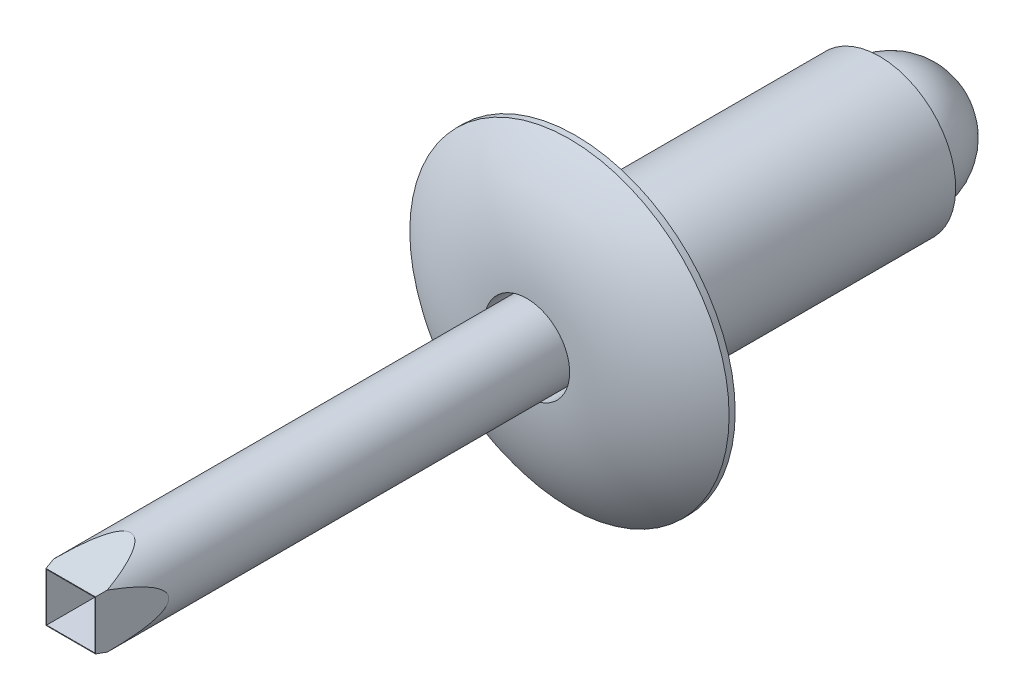
SolidWorks part; units mm, degrees
material "1060 Alloy"
ref_plane "Front" through (0, 0, 0) normal (0, 0, 1) x (1, 0, 0)
ref_plane "Top" through (0, 0, 0) normal (0, 1, 0) x (1, 0, 0)
ref_plane "Right" through (0, 0, 0) normal (1, 0, 0) x (0, 0, -1)
sketch "Sketch1" plane through (0, 0, 0) normal (1, 0, 0) x (0, 0, -1)
  line L0 (-21.082, 0) -> (-2.032, 0) construction
  line L1 (-2.032, 0) -> (0, 0) construction
  line L2 (0, 0) -> (12.7, 0) construction
  line L3 (12.7, 0) -> (15.748, 0) construction
  line L8 (0, 6.6675) -> (0, -6.6675) construction
  line L9 (12.7, 3.175) -> (12.7, -3.175) construction
  dimension "Length" = 12.7
  dimension "Head Height" = 2.032
  dimension "D5" = 3.048
  dimension "D9" = 19.05
  dimension "Diameter" = 6.35
  dimension "Head Diameter" = 13.335
sketch "Sketch2" plane through (0, 0, 0) normal (1, 0, 0) x (0, 0, -1)
  line L0 (-21.082, 1.5875) -> (-21.082, 0) construction
  line L1 (-21.082, 1.5875) -> (0, 1.5875) construction
  line L2 (0, 6.6675) -> (0, -6.6675) construction
  line L3 (0, 0) -> (0, 6.6675) construction
  line L4 (-2.032, 0) -> (-2.032, -1.8472) construction
  line L5 (12.7, 3.175) -> (0, 3.175)
  line L6 (12.7, 3.175) -> (12.7, 0) construction
  line L7 (15.748, 0) -> (15.748, 3.175) construction
  line L8 (12.7, 3.175) -> (12.7, 0)
  line L9 (15.748, 3.175) -> (12.7, 3.175) construction
  line L11 (12.7, 0) -> (15.748, 0) construction
  line L12 (12.7, 0) -> (1.27, 0)
  line L13 (-2.032, 1.5875) -> (-2.032, 0) construction
  line L14 (12.7, 3.175) -> (12.7, 0) construction
  line L15 (12.7, 3.175) -> (12.7, 0) construction
  line L16 (12.7, 0) -> (12.7, 3.175) construction
  line L17 (12.7, 3.175) -> (12.7, 0) construction
  line L18 (12.7, 0) -> (12.7, 3.175) construction
  line L19 (0, 3.175) -> (0, 6.6675)
  line L20 (-2.032, 1.7859) -> (0, 1.7859)
  line L21 (-21.082, 1.7859) -> (0, 1.7859) construction
  line L22 (0, 6.6675) -> (-0.254, 6.6675)
  line L23 (0, 1.7859) -> (1.27, 1.7859)
  line L24 (1.27, 1.7859) -> (1.27, 0)
  arc A0 (15.748, 0) -> (12.7, 2.54) centre (13.1657, 0) ccw construction
  arc A2 (-0.254, 6.6675) -> (-2.032, 1.7859) centre (5.5583, 1.7859) ccw
  dimension "D3" = 0.254
  dimension "D1" = 1.5875
  dimension "D2" = 1.27
  dimension "D5" = 2.54
  dimension "D4" = 0.1984
revolve "Revolve1" add sketch "Sketch2" angle 360 about L12
sketch "Sketch7" plane through (0, 0, 0) normal (1, 0, 0) x (0, 0, -1)
  line L0 (-21.082, 1.5875) -> (1.27, 1.5875)
  line L1 (1.27, 1.7859) -> (1.27, 0) construction
  line L2 (1.27, 1.5875) -> (1.27, 0)
  line L3 (1.27, 0) -> (-21.082, 0)
  line L4 (-21.082, 0) -> (-21.082, 1.5875)
revolve "Revolve2" add sketch "Sketch7" angle 360 about L0
sketch "Sketch8" plane through (0, 0, 0) normal (1, 0, 0) x (0, 0, -1)
  line L1 (12.7, 2.54) -> (12.7, 0)
  line L2 (12.7, 0) -> (15.748, 0)
  arc A0 (15.748, 0) -> (12.7, 2.54) centre (13.1657, 0) ccw construction
  arc A1 (15.748, 0) -> (12.7, 2.54) centre (13.1657, 0) ccw
revolve "Revolve3" add sketch "Sketch8" angle 360 about L3
sketch "Sketch3" plane through (0, 0, 0) normal (0, 1, 0) x (1, 0, 0)
  line L0 (-1.7907, -17.6592) -> (-1.0319, -21.082)
  line L2 (-1.5875, -21.082) -> (1.5875, -21.082) construction
  line L3 (0, -21.082) -> (0, -21.59) construction
  line L4 (-1.0319, -21.082) -> (1.0319, -21.082)
  line L5 (-1.7907, -17.6592) -> (-1.7907, -21.59)
  line L6 (-1.7907, -21.59) -> (1.7907, -21.59)
  line L7 (1.7907, -21.59) -> (1.7907, -17.6592)
  line L8 (-1.5875, 1.27) -> (-1.5875, -21.082) construction
  line L9 (0, -21.082) -> (0, -2.032) construction
  line L10 (1.0319, -21.082) -> (1.7907, -17.6592)
  point P12 (0, -21.082)
  dimension "D3" = 0.508
  dimension "D2" = 0.2032
  dimension "D1" = 25
  dimension "D4" = 2.0638
extrude "Cut-Extrude1" cut sketch "Sketch3" against normal through all both and the other way through all
pattern_circular "CirPattern1" count 2 every 90 about axis through (0, 0, 21.082) along (0, 0, -1) of "Cut-Extrude1"
sketch "Sketch9" plane through (0, 0, 21.082) normal (0, 0, 1) x (1, 0, 0)
  line L8 (-1.0065, -1.0065) -> (1.0065, -1.0065)
  line L9 (1.0065, -1.0065) -> (1.0065, 1.0065)
  line L10 (1.0065, 1.0065) -> (-1.0065, 1.0065)
  line L11 (-1.0065, 1.0065) -> (-1.0065, -1.0065)
  line L12 (-1.0065, -1.0065) -> (1.0065, -1.0065)
  line L13 (1.0065, -1.0065) -> (1.0065, 1.0065)
  line L14 (1.0065, 1.0065) -> (-1.0065, 1.0065)
  line L15 (-1.0065, 1.0065) -> (-1.0065, -1.0065)
  dimension "D1" = 0.0254
extrude "Cut-Extrude3" cut sketch "Sketch9" against normal blind 2.54
fillet "Fillet2" radius 0.254 1 edges at (0, 3.175, 0)
ref_plane "Contact Plane 1" through (0, 0, 0) normal (0, 0, -1) x (-1, 0, 0)
equation "\"D5@Sketch1\" = \"Head Height@Sketch1\" * 1.5"
equation "\"D9@Sketch1\" = \"Length@Sketch1\" * 1.5"
equation "\"D1@Sketch2\"=\"Diameter@Sketch1\"/4"
equation "\"D4@Sketch2\"=\"D1@Sketch2\"/8"
equation "\"D2@Sketch2\"=\"Length@Sketch1\"/10"
equation "\"D4@Sketch3\"=\"D1@Sketch2\"*2*.65"
equation "\"D5@Sketch2\"=\"Diameter@Sketch1\"*.8/2"
